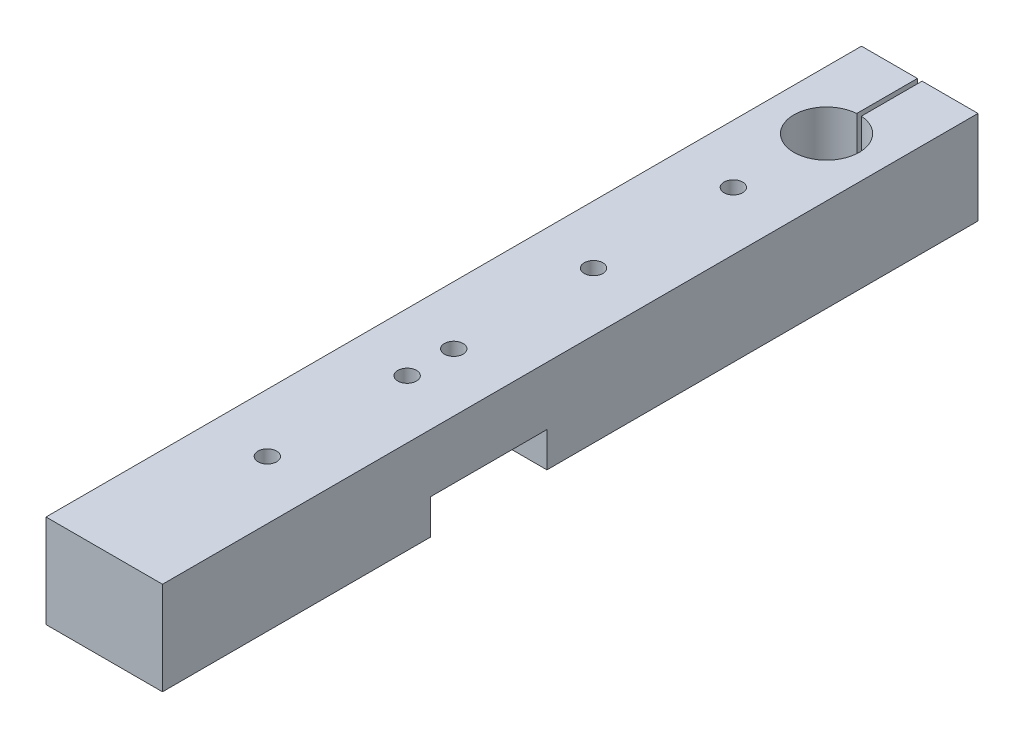
SolidWorks part; units mm, degrees
material "Дуб"
ref_plane "Спереди" through (0, 0, 0) normal (0, 0, 1) x (1, 0, 0)
ref_plane "Сверху" through (0, 0, 0) normal (0, 1, 0) x (1, 0, 0)
ref_plane "Справа" through (0, 0, 0) normal (1, 0, 0) x (0, 0, -1)
sketch "Эскиз1" plane through (0, 0, 0) normal (0, 1, 0) x (1, 0, 0)
  line L1 (0, 0) -> (50, 0)
  line L2 (0, 0) -> (0, 350)
  line L3 (0, 350) -> (24, 350)
  line L4 (50, 0) -> (50, 350)
  line L5 (24, 350) -> (24, 323.9642)
  line L6 (26, 350) -> (26, 323.9642)
  line L7 (26, 350) -> (50, 350)
  arc A0 (24, 323.9642) -> (26, 323.9642) centre (25, 310) ccw
  dimension "D3" = 28
  dimension "D1" = 350
  dimension "D2" = 50
  dimension "D4" = 40
extrude "Бобышка-Вытянуть1" add sketch "Эскиз1" along normal blind 40
sketch "Эскиз2" plane through (0, 40, 0) normal (0, 1, 0) x (1, 0, 0)
  line L0 (25, 0) -> (25, 358.6454) construction
  line L1 (0, 0) -> (50, 0) construction
  line L2 (24, 350) -> (0, 350) construction
  line L3 (50, 350) -> (26, 350) construction
  circle A0 centre (25, 130) radius 4
  circle A1 centre (25, 150) radius 4
  circle A2 centre (25, 270) radius 4
  circle A3 centre (25, 210) radius 4
  circle A4 centre (25, 70) radius 4
  dimension "D1" = 8
  dimension "D2" = 8
  dimension "D5" = 8
  dimension "D6" = 8
  dimension "D7" = 8
  dimension "D3" = 200
  dimension "D4" = 20
  dimension "D8" = 80
  dimension "D9" = 60
  dimension "D10" = 280
extrude "Вырез-Вытянуть1" cut sketch "Эскиз2" against normal blind 50
sketch "Эскиз3" plane through (0, 0, 0) normal (0, -1, 0) x (1, 0, 0)
  line L0 (0, -140) -> (50, -140) construction
  line L1 (0, -350) -> (0, 0) construction
  line L2 (50, 0) -> (50, -350) construction
  line L4 (0, -115) -> (50, -115)
  line L5 (0, -115) -> (0, -165)
  line L6 (0, -165) -> (50, -165)
  line L7 (50, -115) -> (50, -165)
  circle A0 centre (25, -130) radius 4 construction
  dimension "D1" = 10
  dimension "D2" = 25
  dimension "D3" = 50
extrude "Вырез-Вытянуть2" cut sketch "Эскиз3" against normal blind 15
